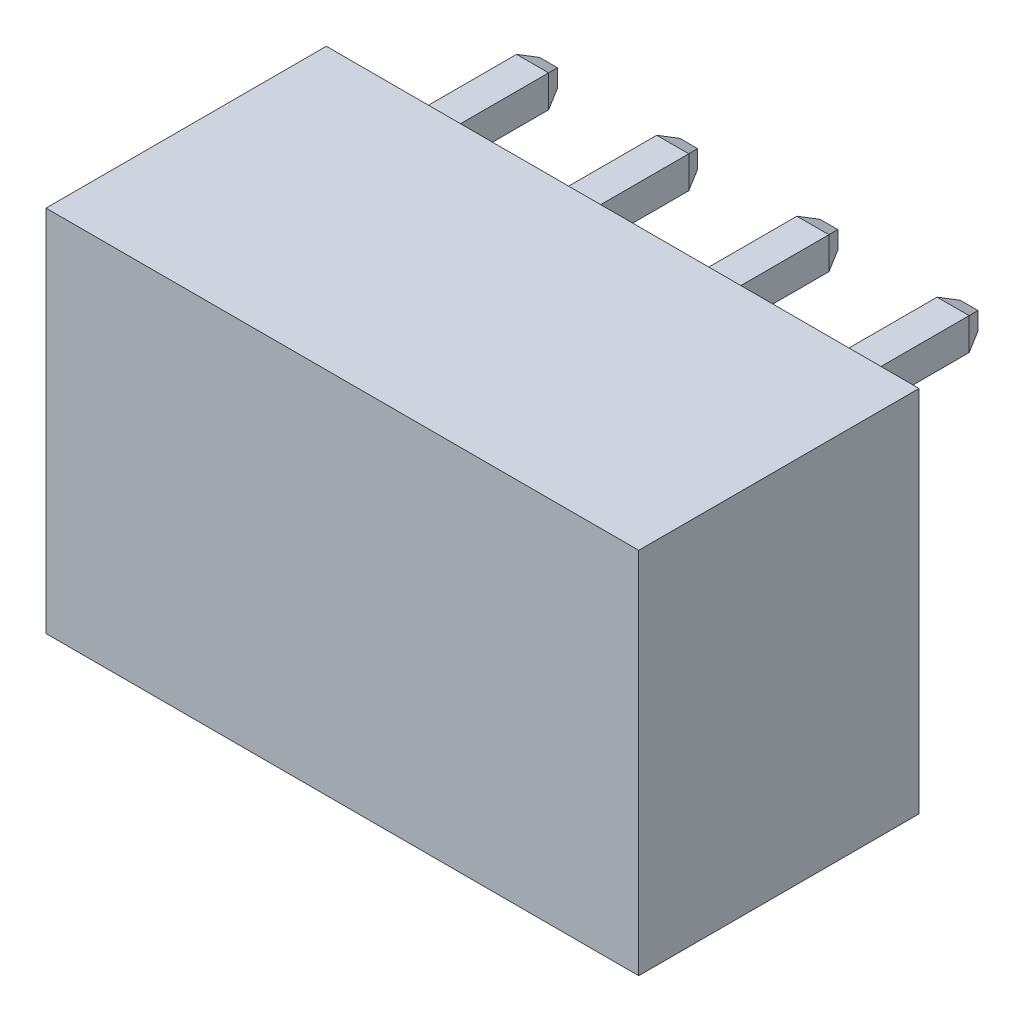
SolidWorks part; units mm, degrees
ref_plane "Спереди" through (0, 0, 0) normal (0, 0, 1) x (1, 0, 0)
ref_plane "Сверху" through (0, 0, 0) normal (0, 1, 0) x (1, 0, 0)
ref_plane "Справа" through (0, 0, 0) normal (1, 0, 0) x (0, 0, -1)
sketch "Эскиз1" plane through (0, 0, 0) normal (0, 0, 1) x (1, 0, 0)
  line L1 (7.4, 9.2) -> (-7.4, 9.2)
  line L2 (7.4, 9.2) -> (7.4, 0)
  line L3 (7.4, 0) -> (-7.4, 0)
  line L4 (-7.4, 9.2) -> (-7.4, 0)
  line L5 (7.4, 9.2) -> (-7.4, 0) construction
  line L6 (7.4, 0) -> (-7.4, 9.2) construction
  point P0 (0, 4.6)
  dimension "D1" = 9.2
  dimension "D2" = 14.8
extrude "Бобышка-Вытянуть1" add sketch "Эскиз1" along normal blind 7
sketch "Эскиз2" plane through (0, 0, 0) normal (0, 0, -1) x (-1, 0, 0)
  line L0 (7.4, 0) -> (-7.4, 0) construction
  line L1 (-5.65, 7.6) -> (-4.85, 7.6)
  line L2 (-5.65, 7.6) -> (-5.65, 8.4)
  line L3 (-5.65, 8.4) -> (-4.85, 8.4)
  line L4 (-4.85, 7.6) -> (-4.85, 8.4)
  line L5 (-5.65, 7.6) -> (-4.85, 8.4) construction
  line L6 (-5.65, 8.4) -> (-4.85, 7.6) construction
  line L7 (-7.4, 0) -> (-7.4, 9.2) construction
  point P0 (-5.25, 8)
  dimension "D1" = 8
  dimension "D2" = 0.8
  dimension "D3" = 2.15
extrude "Бобышка-Вытянуть2" add sketch "Эскиз2" along normal blind 3.4
chamfer "Фаска1" distance 0.4 angle 24 4 edges at (5.25, 8.4, -3.4) (4.85, 8, -3.4) (5.25, 7.6, -3.4) (5.65, 8, -3.4)
sketch "Эскиз3" plane through (0, 0, 0) normal (0, -1, 0) x (1, 0, 0)
  line L1 (3.65, 0.8) -> (6.75, 0.8)
  line L2 (3.65, 0.8) -> (3.65, 5)
  line L4 (6.75, 0.8) -> (6.75, 5)
  line L5 (3.65, 0.8) -> (6.75, 5) construction
  line L6 (3.65, 5) -> (6.75, 0.8) construction
  line L7 (-7.4, 0) -> (7.4, 0) construction
  line L9 (7.4, 7) -> (7.4, 0) construction
  line L10 (-7.4, 7) -> (7.4, 7) construction
  line L11 (3.65, 6.5) -> (6.75, 6.5)
  line L12 (3.65, 5) -> (4.65, 5)
  line L13 (4.65, 5) -> (3.65, 6.5)
  line L14 (6.75, 5) -> (5.75, 5)
  line L15 (5.75, 5) -> (6.75, 6.5)
  point P0 (5.2, 2.9)
  point P5 (5.2, 6.5)
  dimension "D1" = 2.2
  dimension "D2" = 0.8
  dimension "D3" = 2
  dimension "D4" = 3.1
  dimension "D5" = 0.5
  dimension "D6" = 1
extrude "Вырез-Вытянуть1" cut sketch "Эскиз3" against normal blind 7
pattern_linear "Линейный массив1" count 4 spacing 3.5 along (-1, 0, 0) of "Бобышка-Вытянуть2", "Фаска1"
pattern_linear "Линейный массив2" count 4 spacing 3.5 along (-1, 0, 0) of "Вырез-Вытянуть1"
sketch "Эскиз4" plane through (0, 7, 0) normal (0, -1, 0) x (1, 0, 0)
  line L0 (5.65, -3) -> (5.65, 0) construction
  line L1 (4.85, 3.4) -> (5.65, 3.4)
  line L2 (4.85, 3.4) -> (4.85, 2.6)
  line L3 (4.85, 2.6) -> (5.65, 2.6)
  line L4 (5.65, 3.4) -> (5.65, 2.6)
  line L5 (4.85, 3.4) -> (5.65, 2.6) construction
  line L6 (4.85, 2.6) -> (5.65, 3.4) construction
  line L7 (4.85, -3) -> (4.85, 0) construction
  line L8 (-7.4, 0) -> (7.4, 0) construction
  point P0 (5.25, 3)
  dimension "D1" = 3
extrude "Бобышка-Вытянуть3" add sketch "Эскиз4" along normal blind 6
chamfer "Фаска2" distance 0.4 angle 24 4 edges at (5.65, 1, 3) (5.25, 1, 3.4) (4.85, 1, 3) (5.25, 1, 2.6)
pattern_linear "Линейный массив3" count 4 spacing 3.5 along (-1, 0, 0) of "Фаска2", "Бобышка-Вытянуть3"
equation "\"n\"= 4"
equation "\"width\"= 3.5 * ( \"n\" - 1 ) + 4.3"
equation "\"D2@Эскиз1\" = 3.5 * ( \"n\" - 1 ) + 4.3"
equation "\"D1@Линейный массив1\"=\"n\""
equation "\"D1@Линейный массив2\"=\"n\""
equation "\"D1@Линейный массив3\"=\"n\""
